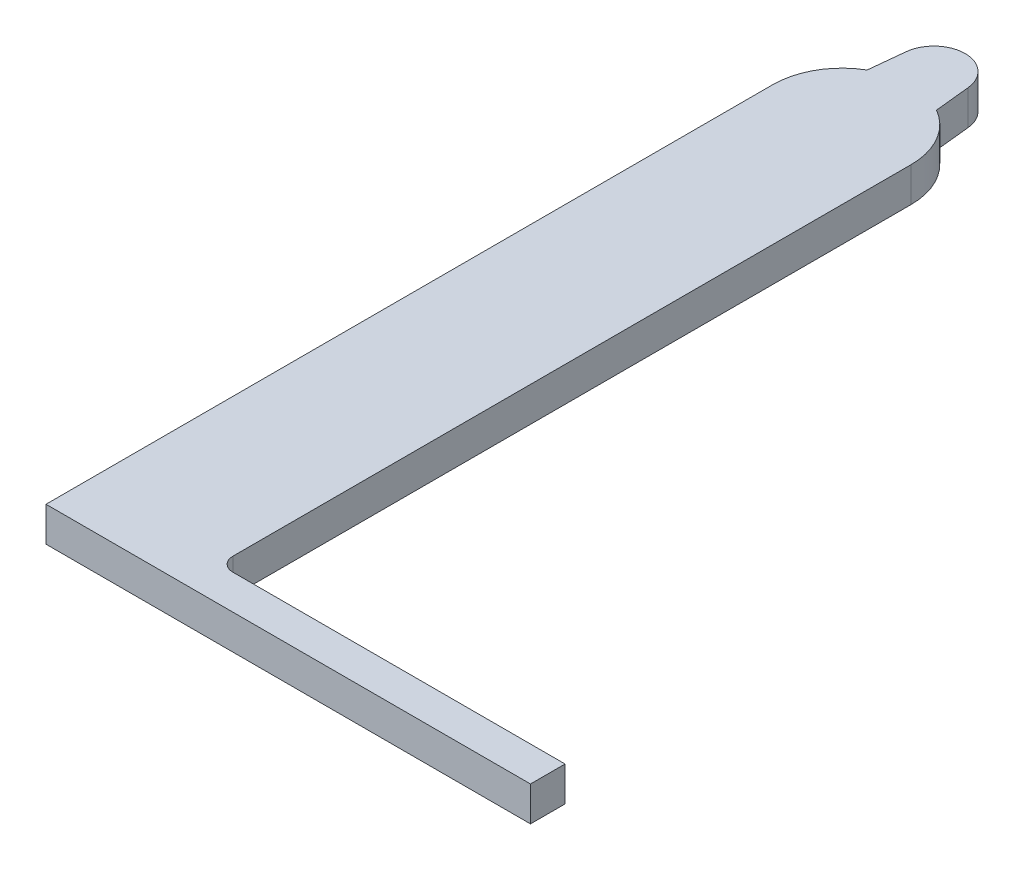
SolidWorks part; units mm, degrees
ref_plane "Front Plane" through (0, 0, 0) normal (0, 0, 1) x (1, 0, 0)
ref_plane "Top Plane" through (0, 0, 0) normal (0, 1, 0) x (1, 0, 0)
ref_plane "Right Plane" through (0, 0, 0) normal (1, 0, 0) x (0, 0, -1)
sketch "Sketch1" plane through (0, 0, 0) normal (0, 1, 0) x (1, 0, 0)
  line L1 (-12.7, 0) -> (12.7, 0)
  line L2 (-12.7, 0) -> (-12.7, -127)
  line L3 (-12.7, -127) -> (12.7, -127)
  line L4 (12.7, 0) -> (12.7, -127)
  circle A0 centre (0, 0) radius 12.7
  dimension "D1" = 25.4
  dimension "D2" = 127
extrude "Boss-Extrude1" add sketch "Sketch1" along normal blind 6.35 contours A0 L2 L3 L4 | L1 A0 | L1 A0
sketch "Sketch2" plane through (0, 6.35, 0) normal (0, 1, 0) x (1, 0, 0)
  line L1 (-12.7, -127) -> (76.2, -127)
  line L2 (-12.7, -127) -> (-12.7, -133.35)
  line L3 (-12.7, -133.35) -> (76.2, -133.35)
  line L4 (76.2, -127) -> (76.2, -133.35)
  dimension "D1" = 88.9
  dimension "D2" = 6.35
extrude "Boss-Extrude2" add sketch "Sketch2" against normal up to surface (6.35 mm away) up to face at (0, 0, 60.325)
fillet "Fillet1" radius 2.54 1 edges
sketch "Sketch3" plane through (0, 0, 0) normal (0, -1, 0) x (-1, 0, 0)
  line L4 (-7.3841, 1.2138) -> (7.3841, 1.2138)
  line L6 (-7.3841, 1.2138) -> (-5.6981, 17.4684)
  line L7 (5.6981, 17.4684) -> (7.3841, 1.2138)
  line L8 (-7.3841, 1.2138) -> (-5.6981, 17.4684)
  line L9 (5.6981, 17.4684) -> (7.3841, 1.2138)
  arc A3 (5.6981, 17.4684) -> (-5.6981, 17.4684) centre (0, 16.8774) ccw
  arc A4 (5.6981, 17.4684) -> (-5.6981, 17.4684) centre (0, 16.8774) ccw
  dimension "D1" = 3.175
extrude "Boss-Extrude3" add sketch "Sketch3" against normal up to surface (6.35 mm away) up to face at (28.2277, 6.35, 81.5366)
